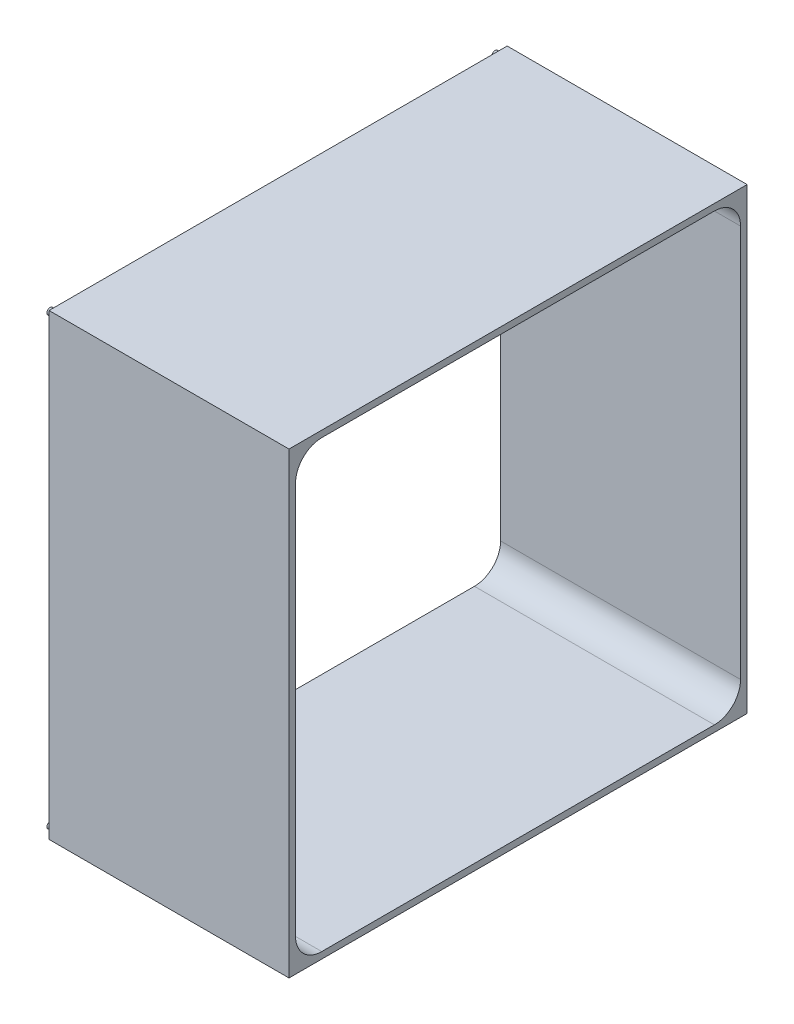
SolidWorks part; units mm, degrees
ref_plane "Front Plane" through (0, 0, 0) normal (0, 0, 1) x (1, 0, 0)
ref_plane "Top Plane" through (0, 0, 0) normal (0, 1, 0) x (1, 0, 0)
ref_plane "Right Plane" through (0, 0, 0) normal (1, 0, 0) x (0, 0, -1)
sketch "Sketch1" plane through (0, 0, 0) normal (1, 0, 0) x (0, 0, -1)
  line L1 (-105, 105) -> (105, 105)
  line L2 (-105, 105) -> (-105, -105)
  line L3 (-105, -105) -> (105, -105)
  line L4 (105, 105) -> (105, -105)
  line L5 (-105, 105) -> (105, -105) construction
  line L6 (-105, -105) -> (105, 105) construction
  point P0 (0, 0)
  dimension "D1" = 210
  dimension "D2" = 210
extrude "Boss-Extrude1" add sketch "Sketch1" along normal blind 110
sketch "Sketch2" plane through (110, 0, 0) normal (1, 0, 0) x (0, 0, -1)
  line L8 (102, -102) -> (102, 102)
  line L9 (102, 102) -> (-102, 102)
  line L10 (-102, 102) -> (-102, -102)
  line L11 (-102, -102) -> (102, -102)
  line L12 (102, -102) -> (102, 102)
  line L13 (102, 102) -> (-102, 102)
  line L14 (-102, 102) -> (-102, -102)
  line L15 (-102, -102) -> (102, -102)
  dimension "D1" = 3
extrude "Cut-Extrude1" cut sketch "Sketch2" against normal blind 110
fillet "Fillet1" radius 12 4 edges at (55, -102, -102) (55, 102, -102) (55, -102, 102) (55, 102, 102)
sketch "Sketch3" plane through (0, 0, 0) normal (-1, 0, 0) x (0, 0, 1)
  line L0 (-105, 105) -> (105, 105) construction
  line L1 (-105, -105) -> (-105, 105) construction
  circle A0 centre (-102, 102) radius 1.5
  dimension "D1" = 3
  dimension "D2" = 3
  dimension "D3" = 3
extrude "Boss-Extrude2" add sketch "Sketch3" along normal blind 2.5
mirror "Mirror1" about plane through (0, 0, 0) normal (0, 0, 1) of "Boss-Extrude2"
mirror "Mirror2" about plane through (0, 0, 0) normal (0, 1, 0) of "Boss-Extrude2", "Mirror1"
